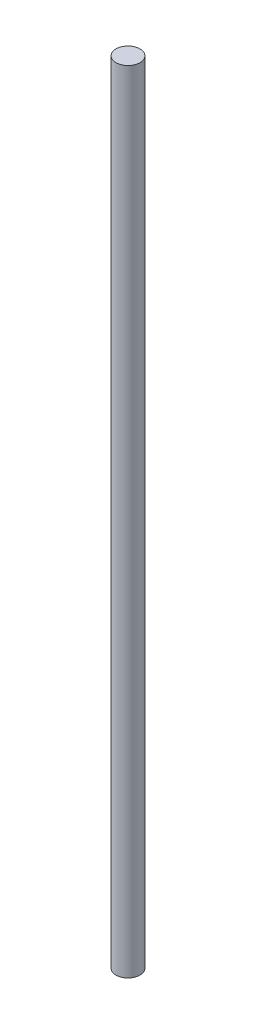
SolidWorks part; units mm, degrees
ref_plane "Front Plane" through (0, 0, 0) normal (0, 0, 1) x (1, 0, 0)
ref_plane "Top Plane" through (0, 0, 0) normal (0, 1, 0) x (1, 0, 0)
ref_plane "Right Plane" through (0, 0, 0) normal (1, 0, 0) x (0, 0, -1)
sketch "Sketch1" plane through (0, 0, 0) normal (0, 1, 0) x (1, 0, 0)
  circle A0 centre (0, 0) radius 4
extrude "Boss-Extrude1" add sketch "Sketch1" along normal blind 264
